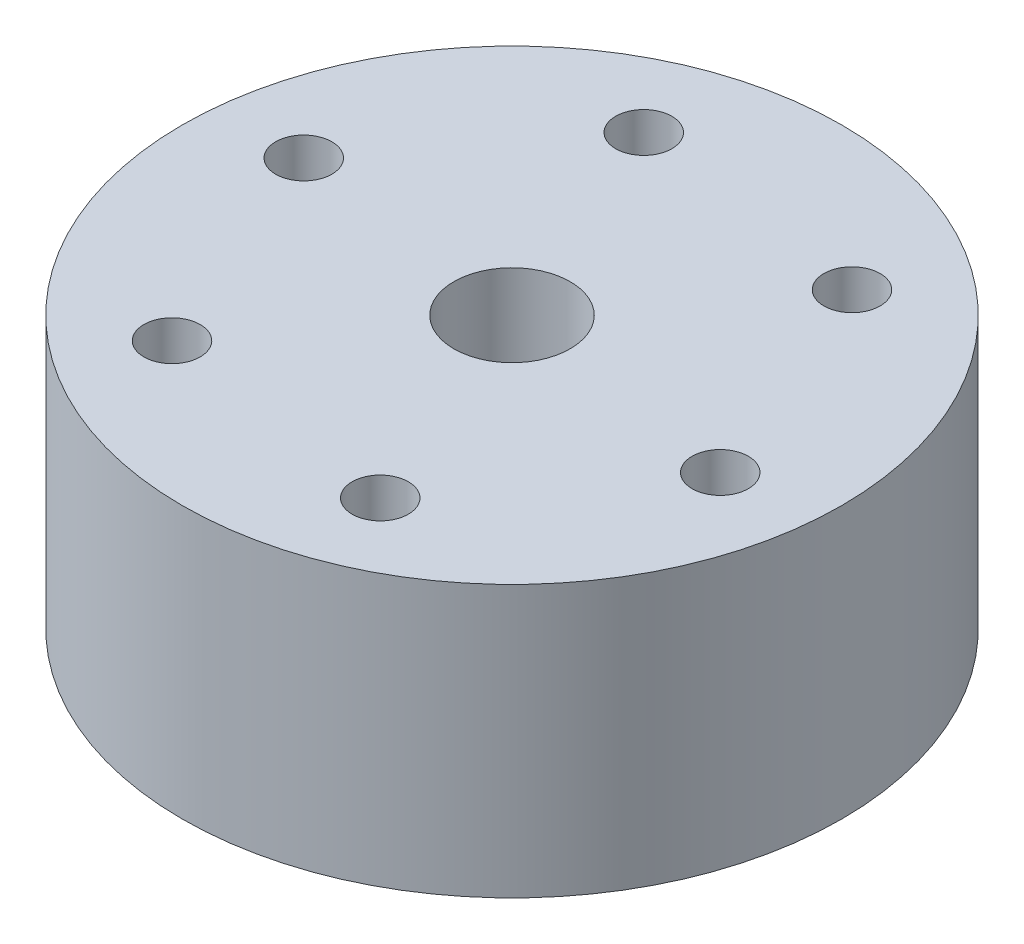
SolidWorks part; units mm, degrees
material "Aleación 6061"
ref_plane "Alzado" through (0, 0, 0) normal (0, 0, 1) x (1, 0, 0)
ref_plane "Planta" through (0, 0, 0) normal (0, 1, 0) x (1, 0, 0)
ref_plane "Vista lateral" through (0, 0, 0) normal (1, 0, 0) x (0, 0, -1)
sketch "Sk_Cubo" plane through (0, 0, 0) normal (0, 1, 0) x (1, 0, 0)
  circle A0 centre (0, -490) radius 17
  dimension "D1" = 34
  dimension "D2" = 490
extrude "Cubo" add sketch "Sk_Cubo" along normal blind 14 from offset 20.5
sketch "Sk_Pasantes_M2-5" plane through (0, 0, 0) normal (0, 1, 0) x (1, 0, 0)
  circle A0 centre (12.3902, -491.6532) radius 1.45
  circle A1 centre (4.7634, -501.5568) radius 1.45
  circle A2 centre (-7.6268, -499.9036) radius 1.45
  circle A3 centre (-12.3902, -488.3468) radius 1.45
  circle A4 centre (-4.7634, -478.4432) radius 1.45
  circle A5 centre (7.6268, -480.0964) radius 1.45
  dimension "D1" = 2.9
  dimension "D4" = 2.9
  dimension "D7" = 2.9
  dimension "D10" = 2.9
  dimension "D13" = 2.9
  dimension "D16" = 2.9
  dimension "D2" = 12.3902
  dimension "D3" = 491.6532
  dimension "D5" = 4.7634
  dimension "D6" = 501.5568
  dimension "D8" = 7.6268
  dimension "D9" = 499.9036
  dimension "D11" = 12.3902
  dimension "D12" = 488.3468
  dimension "D14" = 4.7634
  dimension "D15" = 478.4432
  dimension "D17" = 7.6268
  dimension "D18" = 480.0964
extrude "Pasantes_M2-5" cut sketch "Sk_Pasantes_M2-5" along normal blind 14 from offset 20.5
sketch "Sk_Centro" plane through (0, 0, 0) normal (0, 1, 0) x (1, 0, 0)
  circle A0 centre (0, -490) radius 3
  dimension "D1" = 6
  dimension "D2" = 490
extrude "Centro" cut sketch "Sk_Centro" along normal blind 14 from offset 20.5
